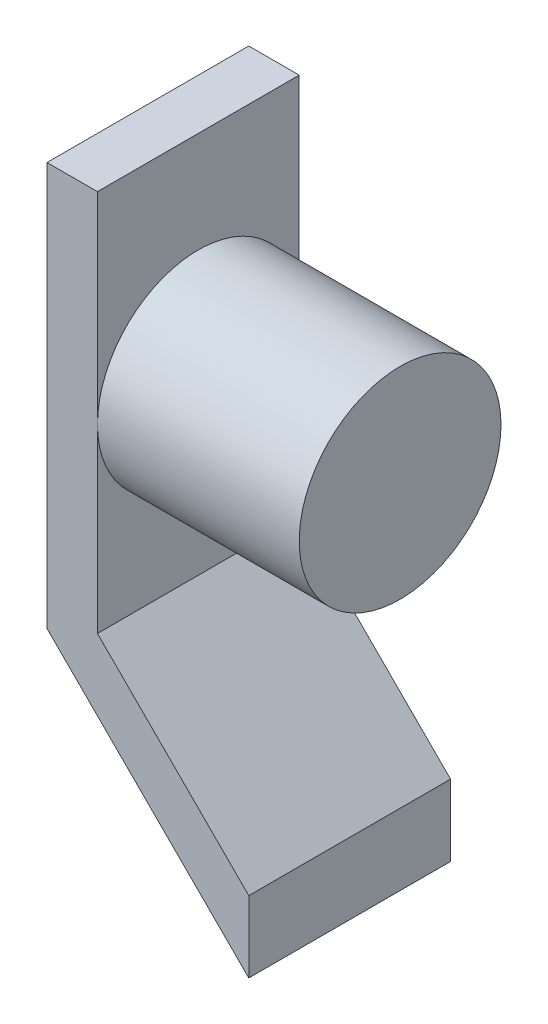
SolidWorks part; units mm, degrees
ref_plane "Front Plane" through (0, 0, 0) normal (0, 0, 1) x (1, 0, 0)
ref_plane "Top Plane" through (0, 0, 0) normal (0, 1, 0) x (1, 0, 0)
ref_plane "Right Plane" through (0, 0, 0) normal (1, 0, 0) x (0, 0, -1)
sketch "Sketch1" plane through (0, 0, 0) normal (0, 0, 1) x (1, 0, 0)
  line L2 (0, 0) -> (0, 25.4)
  line L3 (0, 25.4) -> (3.175, 25.4)
  line L4 (12.7, -12.7) -> (12.7, -8.2099)
  line L5 (12.7, -12.7) -> (0, 0)
  line L6 (9.525, -5.0349) -> (3.175, 1.3151)
  line L7 (3.175, 1.3151) -> (3.175, 22.225)
  line L8 (3.175, 22.225) -> (3.175, 25.4)
  line L9 (9.525, -5.0349) -> (12.7, -8.2099)
  line L10 (0, 25.4) -> (12.7, 25.4) construction
  line L11 (12.7, -12.7) -> (12.7, 25.4) construction
  line L12 (9.525, -5.0349) -> (9.525, 22.225) construction
  line L13 (3.175, 22.225) -> (9.525, 22.225) construction
  dimension "D1" = 12.7
  dimension "D2" = 25.4
  dimension "D3" = 12.7
  dimension "D4" = 3.175
extrude "Boss-Extrude1" add sketch "Sketch1" along normal blind 12.7
sketch "Sketch2" plane through (3.175, 0, 0) normal (1, 0, 0) x (0, 0, -1)
  line L0 (-12.7, 1.3151) -> (-12.7, 25.4) construction
  line L1 (-12.7, 25.4) -> (0, 25.4) construction
  circle A0 centre (-6.35, 12.7) radius 6.35
  point P2 (-12.7, 13.3576)
  point P5 (-6.35, 25.4)
  dimension "D1" = 12.7
  dimension "D2" = 6.35
  dimension "D3" = 12.7
extrude "Boss-Extrude2" add sketch "Sketch2" along normal blind 12.7
